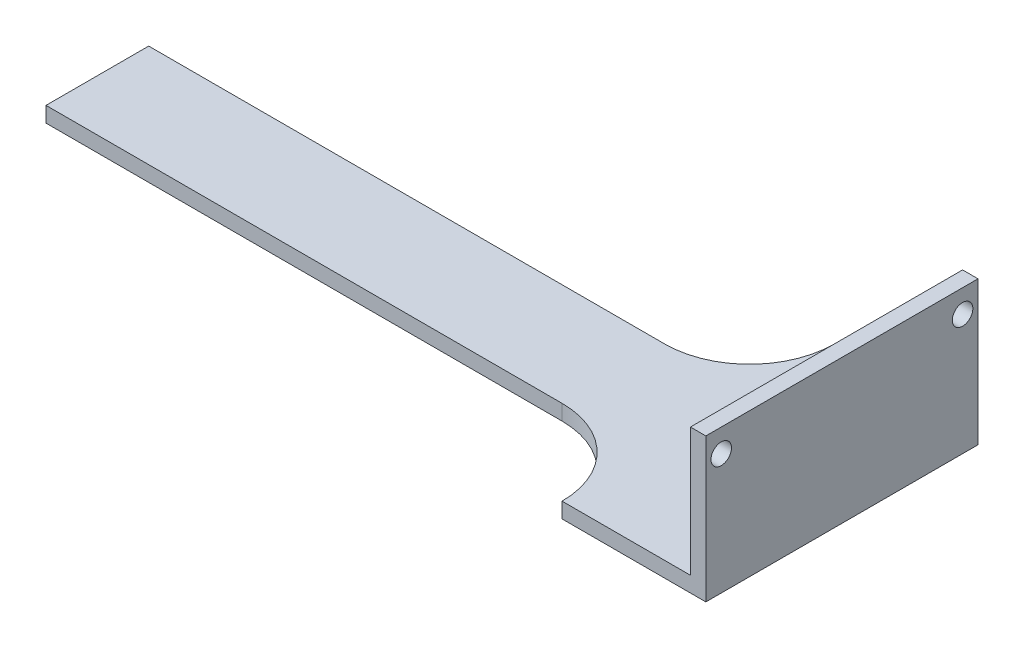
SolidWorks part; units mm, degrees
ref_plane "前视基准面" through (0, 0, 0) normal (0, 0, 1) x (1, 0, 0)
ref_plane "上视基准面" through (0, 0, 0) normal (0, 1, 0) x (1, 0, 0)
ref_plane "右视基准面" through (0, 0, 0) normal (1, 0, 0) x (0, 0, -1)
sketch "草图1" plane through (0, 0, 0) normal (0, 1, 0) x (1, 0, 0)
  line L0 (0, 26.5) -> (142, 26.5) construction
  line L1 (117, 0) -> (142, 0)
  line L2 (0, 16.5) -> (0, 36.5)
  line L3 (117, 53) -> (142, 53)
  line L4 (142, 0) -> (142, 53)
  line L5 (0, 36.5) -> (100.5, 36.5)
  line L7 (0, 16.5) -> (100.5, 16.5)
  arc A0 (100.5, 36.5) -> (117, 53) centre (100.5, 53) ccw
  arc A1 (100.5, 16.5) -> (117, 0) centre (100.5, 0) cw
  dimension "D2" = 142
  dimension "D3" = 10
  dimension "D4" = 25
  dimension "D5" = 53
extrude "凸台-拉伸1" add sketch "草图1" along normal blind 3
sketch "草图2" plane through (142, 0, 0) normal (1, 0, 0) x (0, 0, -1)
  line L1 (0, 0) -> (53, 0)
  line L2 (0, 0) -> (0, 28)
  line L3 (0, 28) -> (53, 28)
  line L4 (53, 0) -> (53, 28)
  dimension "D1" = 28
extrude "凸台-拉伸2" add sketch "草图2" along normal blind 3
sketch "草图3" plane through (145, 0, 0) normal (1, 0, 0) x (0, 0, -1)
  line L0 (26.5, 28) -> (26.5, 0) construction
  line L1 (53, 28) -> (0, 28) construction
  line L2 (0, 0) -> (53, 0) construction
  circle A0 centre (50, 23.5) radius 2
  circle A1 centre (3, 23.5) radius 2
  dimension "D1" = 23.5
  dimension "D2" = 4
  dimension "D3" = 47
extrude "切除-拉伸1" cut sketch "草图3" against normal through all
